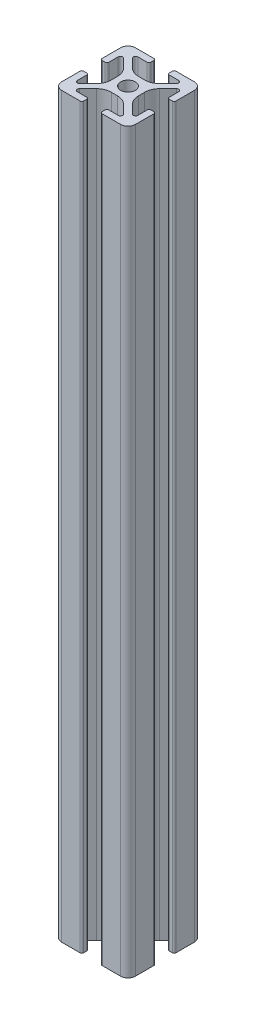
SolidWorks part; units mm, degrees
ref_plane "Front Plane" through (0, 0, 0) normal (0, 0, 1) x (1, 0, 0)
ref_plane "Top Plane" through (0, 0, 0) normal (0, 1, 0) x (1, 0, 0)
ref_plane "Right Plane" through (0, 0, 0) normal (1, 0, 0) x (0, 0, -1)
sketch "Sketch1" plane through (0, 0, 0) normal (0, 1, 0) x (1, 0, 0)
  line L0 (2.8243, 15.9737) -> (5.1284, 13.6695)
  line L1 (2, 0) -> (7, 0)
  line L2 (0, 2) -> (0, 7)
  line L3 (2, 20) -> (7, 20)
  line L4 (20, 2) -> (20, 7)
  line L5 (4.4506, 18.2) -> (7, 18.2)
  line L6 (1.8, 15.5494) -> (1.8, 13)
  line L7 (4.4506, 1.8) -> (7, 1.8)
  line L8 (18.2, 15.5494) -> (18.2, 13)
  line L9 (9.1589, 13.7) -> (10.8411, 13.7)
  line L10 (6.3, 10.8411) -> (6.3, 9.1589)
  line L11 (9.1589, 6.3) -> (10.8411, 6.3)
  line L12 (13.7, 10.8411) -> (13.7, 9.1589)
  line L13 (14.8716, 13.6695) -> (17.1757, 15.9737)
  line L14 (17.1757, 4.0263) -> (14.8716, 6.3305)
  line L15 (13.6695, 5.1284) -> (15.9737, 2.8243)
  line L16 (15.9737, 17.1757) -> (13.6695, 14.8716)
  line L17 (5.1284, 6.3305) -> (2.8243, 4.0263)
  line L18 (4.0263, 2.8243) -> (6.3305, 5.1284)
  line L19 (13, 20) -> (18, 20)
  line L20 (18.2, 18.2) -> (13.7, 13.7) construction
  line L21 (6.3, 13.7) -> (1.8, 18.2) construction
  line L22 (6.3305, 14.8716) -> (4.0263, 17.1757)
  line L24 (7.5, 19.5) -> (7.5, 18.7)
  line L26 (12.5, 19.5) -> (12.5, 18.7)
  line L27 (0.5, 12.5) -> (1.3, 12.5)
  line L29 (0.5, 7.5) -> (1.3, 7.5)
  line L31 (19.5, 12.5) -> (18.7, 12.5)
  line L33 (19.5, 7.5) -> (18.7, 7.5)
  line L36 (7.5, 0.5) -> (7.5, 1.3)
  line L38 (12.5, 0.5) -> (12.5, 1.3)
  line L39 (13, 18.2) -> (15.5494, 18.2)
  line L40 (20, 13) -> (20, 18)
  line L41 (18.2, 7) -> (18.2, 4.4506)
  line L42 (0, 13) -> (0, 18)
  line L43 (1.8, 7) -> (1.8, 4.4506)
  line L44 (13, 0) -> (18, 0)
  line L45 (13, 1.8) -> (15.5494, 1.8)
  circle A0 centre (10, 10) radius 2
  arc A1 (2, 0) -> (0, 2) centre (2, 2) cw
  arc A2 (18, 0) -> (20, 2) centre (18, 2) ccw
  arc A3 (18, 20) -> (20, 18) centre (18, 18) cw
  arc A4 (0, 18) -> (2, 20) centre (2, 18) cw
  arc A5 (5.1284, 6.3305) -> (6.3, 9.1589) centre (2.3, 9.1589) ccw
  arc A6 (6.3305, 5.1284) -> (9.1589, 6.3) centre (9.1589, 2.3) cw
  arc A7 (13.6695, 5.1284) -> (10.8411, 6.3) centre (10.8411, 2.3) ccw
  arc A8 (14.8716, 6.3305) -> (13.7, 9.1589) centre (17.7, 9.1589) cw
  arc A9 (14.8716, 13.6695) -> (13.7, 10.8411) centre (17.7, 10.8411) ccw
  arc A10 (13.6695, 14.8716) -> (10.8411, 13.7) centre (10.8411, 17.7) cw
  arc A11 (6.3305, 14.8716) -> (9.1589, 13.7) centre (9.1589, 17.7) ccw
  arc A12 (5.1284, 13.6695) -> (6.3, 10.8411) centre (2.3, 10.8411) cw
  arc A13 (15.9737, 2.8243) -> (15.5494, 1.8) centre (15.5494, 2.4) cw
  arc A14 (2.8243, 4.0263) -> (1.8, 4.4506) centre (2.4, 4.4506) cw
  arc A15 (4.0263, 2.8243) -> (4.4506, 1.8) centre (4.4506, 2.4) ccw
  arc A16 (17.1757, 4.0263) -> (18.2, 4.4506) centre (17.6, 4.4506) ccw
  arc A17 (17.1757, 15.9737) -> (18.2, 15.5494) centre (17.6, 15.5494) cw
  arc A18 (15.9737, 17.1757) -> (15.5494, 18.2) centre (15.5494, 17.6) ccw
  arc A19 (4.4506, 18.2) -> (4.0263, 17.1757) centre (4.4506, 17.6) ccw
  arc A20 (1.8, 15.5494) -> (2.8243, 15.9737) centre (2.4, 15.5494) cw
  arc A21 (1.8, 13) -> (1.3, 12.5) centre (1.3, 13) cw
  arc A22 (0.5, 12.5) -> (0, 13) centre (0.5, 13) cw
  arc A23 (0.5, 7.5) -> (0, 7) centre (0.5, 7) ccw
  arc A24 (1.8, 7) -> (1.3, 7.5) centre (1.3, 7) ccw
  arc A25 (7.5, 0.5) -> (7, 0) centre (7, 0.5) cw
  arc A26 (7, 1.8) -> (7.5, 1.3) centre (7, 1.3) cw
  arc A27 (13, 0) -> (12.5, 0.5) centre (13, 0.5) cw
  arc A28 (13, 1.8) -> (12.5, 1.3) centre (13, 1.3) ccw
  arc A29 (20, 7) -> (19.5, 7.5) centre (19.5, 7) ccw
  arc A30 (18.2, 7) -> (18.7, 7.5) centre (18.7, 7) cw
  arc A31 (20, 13) -> (19.5, 12.5) centre (19.5, 13) cw
  arc A32 (18.2, 13) -> (18.7, 12.5) centre (18.7, 13) ccw
  arc A33 (13, 18.2) -> (12.5, 18.7) centre (13, 18.7) cw
  arc A34 (12.5, 19.5) -> (13, 20) centre (13, 19.5) cw
  arc A35 (7.5, 19.5) -> (7, 20) centre (7, 19.5) ccw
  arc A36 (7, 18.2) -> (7.5, 18.7) centre (7, 18.7) ccw
  point P41 (0, 0)
  point P48 (20, 0)
  point P51 (20, 20)
  point P54 (0, 20)
  point P91 (0, 12.5)
  point P116 (12.5, 20)
  dimension "D3" = 4
  dimension "D4" = 10
  dimension "D5" = 10
  dimension "D9" = 3.7
  dimension "D7" = 2
  dimension "D14" = 4
  dimension "D17" = 0.6
  dimension "D18" = 0.5
  dimension "D1" = 20
  dimension "D2" = 20
  dimension "D6" = 7.4
  dimension "D8" = 3.7
  dimension "D10" = 1.8
  dimension "D11" = 1.8
  dimension "D12" = 1.8
  dimension "D13" = 1.7
  dimension "D15" = 0.85
  dimension "D16" = 1.7
  dimension "D19" = 7.5
  dimension "D20" = 7.5
  dimension "D21" = 7.5
  dimension "D22" = 7.5
extrude "Boss-Extrude1" add sketch "Sketch1" against normal blind 200
